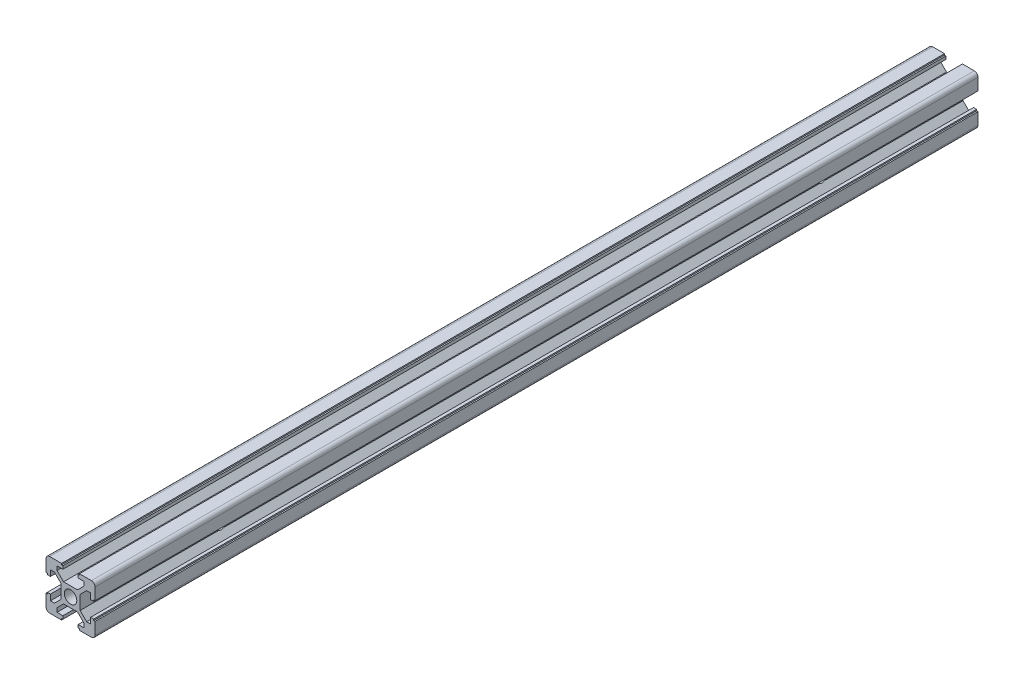
SolidWorks part; units mm, degrees
material "6063-T5"
ref_plane "前视基准面" through (0, 0, 0) normal (0, 0, 1) x (1, 0, 0)
ref_plane "上视基准面" through (0, 0, 0) normal (0, 1, 0) x (1, 0, 0)
ref_plane "右视基准面" through (0, 0, 0) normal (1, 0, 0) x (0, 0, -1)
sketch "草图2" plane through (0, 0, 0) normal (0, 0, 1) x (1, 0, 0)
  line L0 (-3.9, 2.8393) -> (-6.5607, 5.5)
  line L1 (-2.8393, 3.9) -> (2.8393, 3.9)
  line L2 (-3.9, 2.8393) -> (-3.9, -2.8393)
  line L3 (-2.8393, -3.9) -> (2.8393, -3.9)
  line L4 (3.9, 2.8393) -> (3.9, -2.8393)
  line L5 (-3.9, 3.9) -> (3.9, -3.9) construction
  line L6 (-3.9, -3.9) -> (3.9, 3.9) construction
  line L7 (-2.8393, 3.9) -> (-5.5, 6.5607)
  line L8 (-5.5, 6.5607) -> (-5.5, 8.2)
  line L9 (-5.5, 8.2) -> (-3.1, 8.2)
  line L10 (-3.1, 8.2) -> (-3.1, 9.45)
  line L11 (-3.1, 9.45) -> (-3.65, 9.45)
  line L12 (-3.65, 9.45) -> (-3.65, 10)
  line L13 (-3.65, 10) -> (-8.5, 10)
  line L14 (-6.5607, 5.5) -> (-8.2, 5.5)
  line L15 (-10, 3.65) -> (-10, 8.5)
  line L16 (-9.45, 3.65) -> (-10, 3.65)
  line L17 (-9.45, 3.1) -> (-9.45, 3.65)
  line L18 (-8.2, 3.1) -> (-9.45, 3.1)
  line L19 (-8.2, 5.5) -> (-8.2, 3.1)
  line L20 (2.8393, 3.9) -> (5.5, 6.5607)
  line L21 (3.9, 2.8393) -> (6.5607, 5.5)
  line L22 (6.5607, 5.5) -> (8.2, 5.5)
  line L23 (8.2, 5.5) -> (8.2, 3.1)
  line L24 (8.2, 3.1) -> (9.45, 3.1)
  line L25 (9.45, 3.1) -> (9.45, 3.65)
  line L26 (9.45, 3.65) -> (10, 3.65)
  line L27 (10, 3.65) -> (10, 8.5)
  line L28 (5.5, 6.5607) -> (5.5, 8.2)
  line L29 (3.65, 10) -> (8.5, 10)
  line L30 (3.65, 9.45) -> (3.65, 10)
  line L31 (3.1, 9.45) -> (3.65, 9.45)
  line L32 (3.1, 8.2) -> (3.1, 9.45)
  line L33 (5.5, 8.2) -> (3.1, 8.2)
  line L34 (3.9, -2.8393) -> (6.5607, -5.5)
  line L35 (2.8393, -3.9) -> (5.5, -6.5607)
  line L36 (5.5, -6.5607) -> (5.5, -8.2)
  line L37 (5.5, -8.2) -> (3.1, -8.2)
  line L38 (3.1, -8.2) -> (3.1, -9.45)
  line L39 (3.1, -9.45) -> (3.65, -9.45)
  line L40 (3.65, -9.45) -> (3.65, -10)
  line L41 (3.65, -10) -> (8.5, -10)
  line L42 (6.5607, -5.5) -> (8.2, -5.5)
  line L43 (10, -3.65) -> (10, -8.5)
  line L44 (9.45, -3.65) -> (10, -3.65)
  line L45 (9.45, -3.1) -> (9.45, -3.65)
  line L46 (8.2, -3.1) -> (9.45, -3.1)
  line L47 (8.2, -5.5) -> (8.2, -3.1)
  line L48 (-2.8393, -3.9) -> (-5.5, -6.5607)
  line L49 (-3.9, -2.8393) -> (-6.5607, -5.5)
  line L50 (-6.5607, -5.5) -> (-8.2, -5.5)
  line L51 (-8.2, -5.5) -> (-8.2, -3.1)
  line L52 (-8.2, -3.1) -> (-9.45, -3.1)
  line L53 (-9.45, -3.1) -> (-9.45, -3.65)
  line L54 (-9.45, -3.65) -> (-10, -3.65)
  line L55 (-10, -3.65) -> (-10, -8.5)
  line L56 (-5.5, -6.5607) -> (-5.5, -8.2)
  line L57 (-3.65, -10) -> (-8.5, -10)
  line L58 (-3.65, -9.45) -> (-3.65, -10)
  line L59 (-3.1, -9.45) -> (-3.65, -9.45)
  line L60 (-3.1, -8.2) -> (-3.1, -9.45)
  line L61 (-5.5, -8.2) -> (-3.1, -8.2)
  circle A0 centre (0, 0) radius 2.55
  arc A1 (-8.5, 10) -> (-10, 8.5) centre (-8.5, 8.5) ccw
  arc A2 (10, 8.5) -> (8.5, 10) centre (8.5, 8.5) ccw
  arc A3 (8.5, -10) -> (10, -8.5) centre (8.5, -8.5) ccw
  arc A4 (-10, -8.5) -> (-8.5, -10) centre (-8.5, -8.5) ccw
  point P25 (-10, 10)
  point P79 (0, 0)
  dimension "D1" = 5.1
  dimension "D9" = 1.5
  dimension "D2" = 7.8
  dimension "D3" = 1.5
  dimension "D4" = 10
  dimension "D5" = 3.1
  dimension "D6" = 0.55
  dimension "D7" = 1.8
  dimension "D8" = 5.5
  dimension "D11" = 3.9
  dimension "D10" = 4
extrude "凸台-拉伸1" add sketch "草图2" along normal blind 360
sketch "草图3" plane through (10, 0, 0) normal (1, 0, 0) x (0, 0, -1)
  circle A0 centre (-57.5, 0) radius 3
  circle A1 centre (-302.5, 0) radius 3
  dimension "D1" = 6
  dimension "D2" = 6
extrude "切除-拉伸1" cut sketch "草图3" against normal through all
